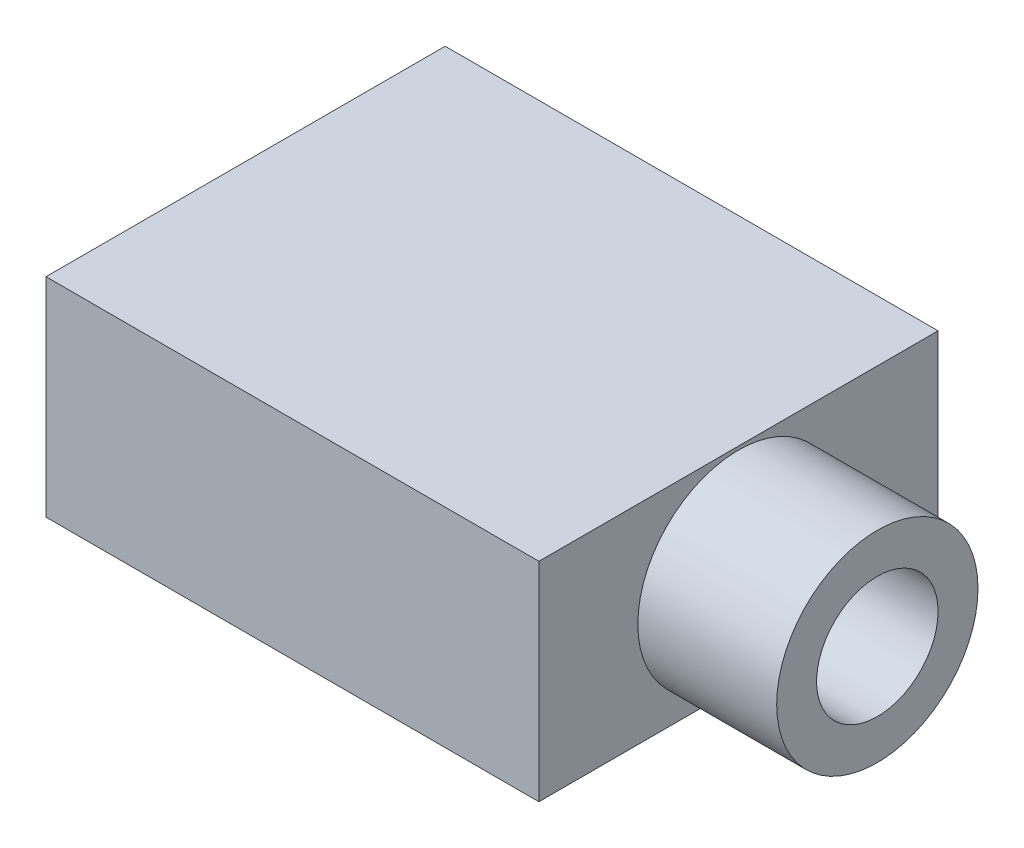
SolidWorks part; units mm, degrees
ref_plane "Front Plane" through (0, 0, 0) normal (0, 0, 1) x (1, 0, 0)
ref_plane "Top Plane" through (0, 0, 0) normal (0, 1, 0) x (1, 0, 0)
ref_plane "Right Plane" through (0, 0, 0) normal (1, 0, 0) x (0, 0, -1)
sketch "Sketch1" plane through (0, 0, 0) normal (0, 1, 0) x (1, 0, 0)
  line L1 (-51.3046, 44.3119) -> (-65.5046, 44.3119)
  line L2 (-51.3046, 44.3119) -> (-51.3046, 32.8119)
  line L3 (-51.3046, 32.8119) -> (-65.5046, 32.8119)
  line L4 (-65.5046, 44.3119) -> (-65.5046, 32.8119)
  dimension "D1" = 14.2
  dimension "D2" = 11.5
extrude "Boss-Extrude1" add sketch "Sketch1" along normal blind 6
sketch "Sketch2" plane through (-51.3046, 0, 0) normal (1, 0, 0) x (0, 0, -1)
  line L0 (32.8119, 6) -> (44.3119, 0) construction
  line L1 (44.3119, 0) -> (44.3119, 6) construction
  line L2 (44.3119, 6) -> (32.8119, 0) construction
  line L3 (32.8119, 0) -> (38.5619, 3) construction
  circle A0 centre (38.5619, 3) radius 2.9
  dimension "D1" = 5.8
extrude "Boss-Extrude2" add sketch "Sketch2" along normal blind 4
sketch "Sketch3" plane through (-47.3046, 0, 0) normal (1, 0, 0) x (0, 0, -1)
  circle A0 centre (38.5619, 3) radius 1.75
  dimension "D1" = 3.5
extrude "Cut-Extrude1" cut sketch "Sketch3" against normal blind 15
